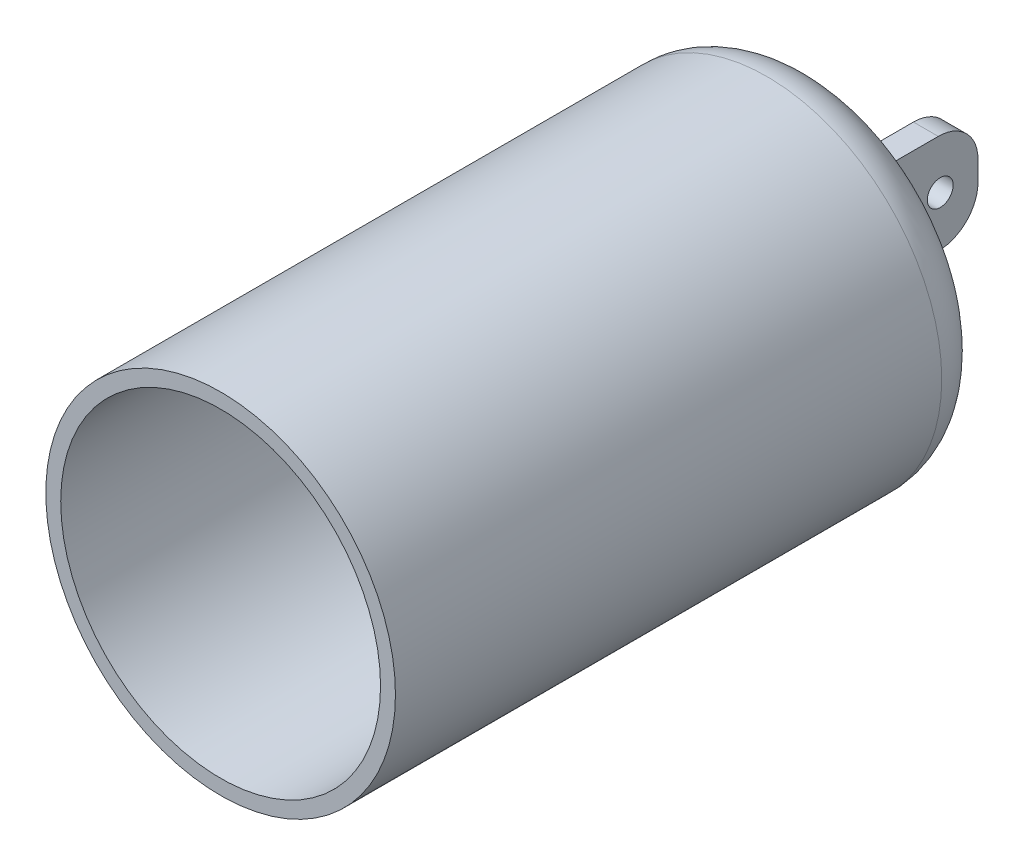
SolidWorks part; units mm, degrees
ref_plane "Front Plane" through (0, 0, 0) normal (0, 0, 1) x (1, 0, 0)
ref_plane "Top Plane" through (0, 0, 0) normal (0, 1, 0) x (1, 0, 0)
ref_plane "Right Plane" through (0, 0, 0) normal (1, 0, 0) x (0, 0, -1)
sketch "Sketch1" plane through (0, 0, 0) normal (0, 0, 1) x (1, 0, 0)
  circle A0 centre (0, 0) radius 136 construction
  circle A1 centre (0, 0) radius 146 construction
  circle A2 centre (0, 0) radius 176
  dimension "D1" = 272
  dimension "D2" = 10
  dimension "D3" = 30
extrude "Boss-Extrude1" add sketch "Sketch1" along normal blind 600
sketch "Sketch2" plane through (0, 0, 0) normal (0, 0, -1) x (-1, 0, 0)
  line L1 (12.5, -50) -> (-12.5, -50)
  line L2 (12.5, -50) -> (12.5, 50)
  line L3 (12.5, 50) -> (-12.5, 50)
  line L4 (-12.5, -50) -> (-12.5, 50)
  line L5 (12.5, -50) -> (-12.5, 50) construction
  line L6 (12.5, 50) -> (-12.5, -50) construction
  point P0 (0, 0)
  dimension "D1" = 25
  dimension "D2" = 100
extrude "Boss-Extrude2" add sketch "Sketch2" along normal blind 150
sketch "Sketch3" plane through (12.5, 0, 0) normal (1, 0, 0) x (0, 0, -1)
  line L0 (112, 0) -> (150, 0) construction
  line L1 (150, 50) -> (150, -50) construction
  line L2 (125, 0) -> (125, 50) construction
  line L3 (150, 50) -> (0, 50) construction
  circle A0 centre (112, 0) radius 13
  dimension "D1" = 26
  dimension "D2" = 25
extrude "Cut-Extrude1" cut sketch "Sketch3" against normal through all
fillet "Fillet1" radius 40 2 edges at (0, 50, -150) (0, -50, -150)
fillet "Fillet3" radius 20 4 edges at (-12.5, 0, 0) (0, -50, 0) (12.5, 0, 0) (0, 50, 0)
fillet "Fillet4" radius 50 1 edges at (176, 0, 0)
shell "Shell1" thickness 15
